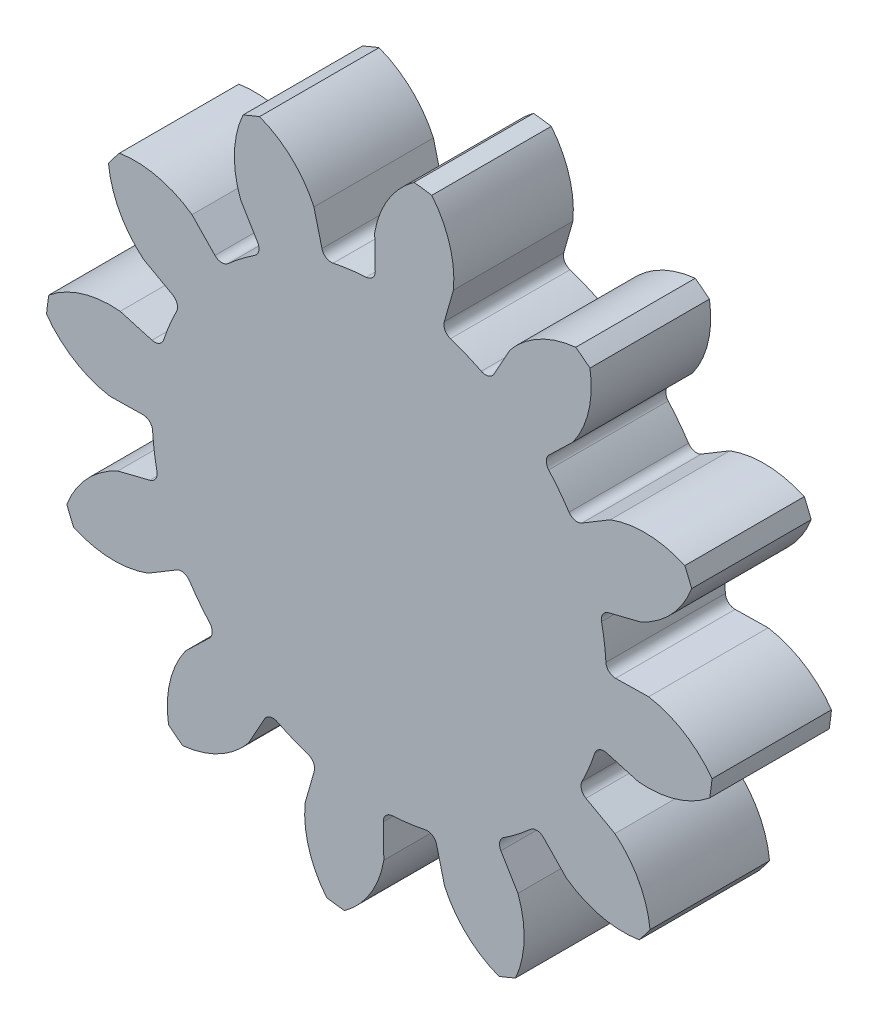
SolidWorks part; units mm, degrees
ref_plane "Front" through (0, 0, 0) normal (0, 0, 1) x (1, 0, 0)
ref_plane "Top" through (0, 0, 0) normal (0, 1, 0) x (1, 0, 0)
ref_plane "Right" through (0, 0, 0) normal (1, 0, 0) x (0, 0, -1)
sketch "草图1" plane through (0, 0, 0) normal (0, 0, 1) x (1, 0, 0)
  line L0 (0, 0) -> (2, 0) construction
  line L21 (0, 0) -> (0, 12) construction
  line L22 (-0.1911, 11.2747) -> (-0.1676, 9.8905)
  line L23 (0, 0) -> (1.8274, 13.8802) construction
  line L24 (0, 0) -> (-1.8274, 13.8802) construction
  line L25 (3.1027, 10.8411) -> (2.7217, 9.5101)
  line L26 (5.4719, 9.8597) -> (4.8001, 8.6492)
  line L27 (8.1075, 7.8373) -> (7.1121, 6.8751)
  line L28 (9.6686, 5.8028) -> (8.4816, 5.0904)
  line L29 (10.94, 2.7336) -> (9.5969, 2.398)
  line L30 (11.2747, 0.1911) -> (9.8905, 0.1676)
  line L31 (10.8411, -3.1027) -> (9.5101, -2.7217)
  line L32 (9.8597, -5.4719) -> (8.6492, -4.8001)
  line L33 (7.8373, -8.1075) -> (6.8751, -7.1121)
  line L34 (5.8028, -9.6686) -> (5.0904, -8.4816)
  line L35 (2.7336, -10.94) -> (2.398, -9.5969)
  line L36 (0.1911, -11.2747) -> (0.1676, -9.8905)
  line L37 (-3.1027, -10.8411) -> (-2.7217, -9.5101)
  line L38 (-5.4719, -9.8597) -> (-4.8001, -8.6492)
  line L39 (-8.1075, -7.8373) -> (-7.1121, -6.8751)
  line L40 (-9.6686, -5.8028) -> (-8.4816, -5.0904)
  line L41 (-10.94, -2.7336) -> (-9.5969, -2.398)
  line L42 (-11.2747, -0.1911) -> (-9.8905, -0.1676)
  line L43 (-10.8411, 3.1027) -> (-9.5101, 2.7217)
  line L44 (-9.8597, 5.4719) -> (-8.6492, 4.8001)
  line L45 (-7.8373, 8.1075) -> (-6.8751, 7.1121)
  line L46 (-5.8028, 9.6686) -> (-5.0904, 8.4816)
  line L47 (-2.7336, 10.94) -> (-2.398, 9.5969)
  circle A0 centre (0, 0) radius 9.5 construction
  circle A1 centre (0, 0) radius 11.2763 construction
  circle A2 centre (0, 0) radius 12 construction
  circle A3 centre (0, 0) radius 14 construction
  arc A4 (0, 12) -> (3.8567, 10.5963) centre (0, 6) cw construction
  arc A5 (0, 12) -> (-0.1911, 11.2747) centre (3.8567, 10.5963) ccw
  arc A6 (0, 12) -> (1.4547, 13.9242) centre (3.8567, 10.5963) cw
  arc A7 (-0.5446, 9.4844) -> (-1.24, 9.4187) centre (0, 0) ccw
  arc A8 (-0.5446, 9.4844) -> (-0.1676, 9.8905) centre (-0.5675, 9.8837) ccw
  arc A9 (1.4547, 13.9242) -> (2.1987, 13.8263) centre (0, 0) cw
  arc A10 (3.1058, 11.5911) -> (2.1987, 13.8263) centre (-0.9828, 11.2334) ccw
  arc A11 (3.1058, 11.5911) -> (3.1027, 10.8411) centre (-0.9828, 11.2334) cw
  arc A12 (2.9808, 9.0202) -> (2.7217, 9.5101) centre (3.1063, 9.4) cw
  arc A13 (2.9808, 9.0202) -> (3.6355, 8.7769) centre (0, 0) cw
  arc A14 (4.2705, 8.486) -> (3.6355, 8.7769) centre (0, 0) ccw
  arc A15 (4.2705, 8.486) -> (4.8001, 8.6492) centre (4.4504, 8.8433) ccw
  arc A16 (6, 10.3923) -> (5.4719, 9.8597) centre (8.6382, 7.2483) ccw
  arc A17 (6, 10.3923) -> (8.2219, 11.3314) centre (8.6382, 7.2483) cw
  arc A18 (8.2219, 11.3314) -> (8.8173, 10.8746) centre (0, 0) cw
  arc A19 (8.4853, 8.4853) -> (8.8173, 10.8746) centre (4.7656, 10.2198) ccw
  arc A20 (8.4853, 8.4853) -> (8.1075, 7.8373) centre (4.7656, 10.2198) cw
  arc A21 (7.0916, 6.3214) -> (7.1121, 6.8751) centre (7.3902, 6.5875) cw
  arc A22 (7.0916, 6.3214) -> (7.5369, 5.7832) centre (0, 0) cw
  arc A23 (7.9414, 5.2138) -> (7.5369, 5.7832) centre (0, 0) ccw
  arc A24 (7.9414, 5.2138) -> (8.4816, 5.0904) centre (8.2758, 5.4334) ccw
  arc A25 (10.3923, 6) -> (9.6686, 5.8028) centre (11.105, 1.9581) ccw
  arc A26 (10.3923, 6) -> (12.7861, 5.7023) centre (11.105, 1.9581) cw
  arc A27 (12.7861, 5.7023) -> (13.0732, 5.009) centre (0, 0) cw
  arc A28 (11.5911, 3.1058) -> (13.0732, 5.009) centre (9.237, 6.4678) ccw
  arc A29 (11.5911, 3.1058) -> (10.94, 2.7336) centre (9.237, 6.4678) cw
  arc A30 (9.3022, 1.9287) -> (9.5969, 2.398) centre (9.6938, 2.0099) cw
  arc A31 (9.3022, 1.9287) -> (9.4187, 1.24) centre (0, 0) cw
  arc A32 (9.4844, 0.5446) -> (9.4187, 1.24) centre (0, 0) ccw
  arc A33 (9.4844, 0.5446) -> (9.8905, 0.1676) centre (9.8837, 0.5675) ccw
  arc A34 (12, 0) -> (11.2747, 0.1911) centre (10.5963, -3.8567) ccw
  arc A35 (12, 0) -> (13.9242, -1.4547) centre (10.5963, -3.8567) cw
  arc A36 (13.9242, -1.4547) -> (13.8263, -2.1987) centre (0, 0) cw
  arc A37 (11.5911, -3.1058) -> (13.8263, -2.1987) centre (11.2334, 0.9828) ccw
  arc A38 (11.5911, -3.1058) -> (10.8411, -3.1027) centre (11.2334, 0.9828) cw
  arc A39 (9.0202, -2.9808) -> (9.5101, -2.7217) centre (9.4, -3.1063) cw
  arc A40 (9.0202, -2.9808) -> (8.7769, -3.6355) centre (0, 0) cw
  arc A41 (8.486, -4.2705) -> (8.7769, -3.6355) centre (0, 0) ccw
  arc A42 (8.486, -4.2705) -> (8.6492, -4.8001) centre (8.8433, -4.4504) ccw
  arc A43 (10.3923, -6) -> (9.8597, -5.4719) centre (7.2483, -8.6382) ccw
  arc A44 (10.3923, -6) -> (11.3314, -8.2219) centre (7.2483, -8.6382) cw
  arc A45 (11.3314, -8.2219) -> (10.8746, -8.8173) centre (0, 0) cw
  arc A46 (8.4853, -8.4853) -> (10.8746, -8.8173) centre (10.2198, -4.7656) ccw
  arc A47 (8.4853, -8.4853) -> (7.8373, -8.1075) centre (10.2198, -4.7656) cw
  arc A48 (6.3214, -7.0916) -> (6.8751, -7.1121) centre (6.5875, -7.3902) cw
  arc A49 (6.3214, -7.0916) -> (5.7832, -7.5369) centre (0, 0) cw
  arc A50 (5.2138, -7.9414) -> (5.7832, -7.5369) centre (0, 0) ccw
  arc A51 (5.2138, -7.9414) -> (5.0904, -8.4816) centre (5.4334, -8.2758) ccw
  arc A52 (6, -10.3923) -> (5.8028, -9.6686) centre (1.9581, -11.105) ccw
  arc A53 (6, -10.3923) -> (5.7023, -12.7861) centre (1.9581, -11.105) cw
  arc A54 (5.7023, -12.7861) -> (5.009, -13.0732) centre (0, 0) cw
  arc A55 (3.1058, -11.5911) -> (5.009, -13.0732) centre (6.4678, -9.237) ccw
  arc A56 (3.1058, -11.5911) -> (2.7336, -10.94) centre (6.4678, -9.237) cw
  arc A57 (1.9287, -9.3022) -> (2.398, -9.5969) centre (2.0099, -9.6938) cw
  arc A58 (1.9287, -9.3022) -> (1.24, -9.4187) centre (0, 0) cw
  arc A59 (0.5446, -9.4844) -> (1.24, -9.4187) centre (0, 0) ccw
  arc A60 (0.5446, -9.4844) -> (0.1676, -9.8905) centre (0.5675, -9.8837) ccw
  arc A61 (0, -12) -> (0.1911, -11.2747) centre (-3.8567, -10.5963) ccw
  arc A62 (0, -12) -> (-1.4547, -13.9242) centre (-3.8567, -10.5963) cw
  arc A63 (-1.4547, -13.9242) -> (-2.1987, -13.8263) centre (0, 0) cw
  arc A64 (-3.1058, -11.5911) -> (-2.1987, -13.8263) centre (0.9828, -11.2334) ccw
  arc A65 (-3.1058, -11.5911) -> (-3.1027, -10.8411) centre (0.9828, -11.2334) cw
  arc A66 (-2.9808, -9.0202) -> (-2.7217, -9.5101) centre (-3.1063, -9.4) cw
  arc A67 (-2.9808, -9.0202) -> (-3.6355, -8.7769) centre (0, 0) cw
  arc A68 (-4.2705, -8.486) -> (-3.6355, -8.7769) centre (0, 0) ccw
  arc A69 (-4.2705, -8.486) -> (-4.8001, -8.6492) centre (-4.4504, -8.8433) ccw
  arc A70 (-6, -10.3923) -> (-5.4719, -9.8597) centre (-8.6382, -7.2483) ccw
  arc A71 (-6, -10.3923) -> (-8.2219, -11.3314) centre (-8.6382, -7.2483) cw
  arc A72 (-8.2219, -11.3314) -> (-8.8173, -10.8746) centre (0, 0) cw
  arc A73 (-8.4853, -8.4853) -> (-8.8173, -10.8746) centre (-4.7656, -10.2198) ccw
  arc A74 (-8.4853, -8.4853) -> (-8.1075, -7.8373) centre (-4.7656, -10.2198) cw
  arc A75 (-7.0916, -6.3214) -> (-7.1121, -6.8751) centre (-7.3902, -6.5875) cw
  arc A76 (-7.0916, -6.3214) -> (-7.5369, -5.7832) centre (0, 0) cw
  arc A77 (-7.9414, -5.2138) -> (-7.5369, -5.7832) centre (0, 0) ccw
  arc A78 (-7.9414, -5.2138) -> (-8.4816, -5.0904) centre (-8.2758, -5.4334) ccw
  arc A79 (-10.3923, -6) -> (-9.6686, -5.8028) centre (-11.105, -1.9581) ccw
  arc A80 (-10.3923, -6) -> (-12.7861, -5.7023) centre (-11.105, -1.9581) cw
  arc A81 (-12.7861, -5.7023) -> (-13.0732, -5.009) centre (0, 0) cw
  arc A82 (-11.5911, -3.1058) -> (-13.0732, -5.009) centre (-9.237, -6.4678) ccw
  arc A83 (-11.5911, -3.1058) -> (-10.94, -2.7336) centre (-9.237, -6.4678) cw
  arc A84 (-9.3022, -1.9287) -> (-9.5969, -2.398) centre (-9.6938, -2.0099) cw
  arc A85 (-9.3022, -1.9287) -> (-9.4187, -1.24) centre (0, 0) cw
  arc A86 (-9.4844, -0.5446) -> (-9.4187, -1.24) centre (0, 0) ccw
  arc A87 (-9.4844, -0.5446) -> (-9.8905, -0.1676) centre (-9.8837, -0.5675) ccw
  arc A88 (-12, 0) -> (-11.2747, -0.1911) centre (-10.5963, 3.8567) ccw
  arc A89 (-12, 0) -> (-13.9242, 1.4547) centre (-10.5963, 3.8567) cw
  arc A90 (-13.9242, 1.4547) -> (-13.8263, 2.1987) centre (0, 0) cw
  arc A91 (-11.5911, 3.1058) -> (-13.8263, 2.1987) centre (-11.2334, -0.9828) ccw
  arc A92 (-11.5911, 3.1058) -> (-10.8411, 3.1027) centre (-11.2334, -0.9828) cw
  arc A93 (-9.0202, 2.9808) -> (-9.5101, 2.7217) centre (-9.4, 3.1063) cw
  arc A94 (-9.0202, 2.9808) -> (-8.7769, 3.6355) centre (0, 0) cw
  arc A95 (-8.486, 4.2705) -> (-8.7769, 3.6355) centre (0, 0) ccw
  arc A96 (-8.486, 4.2705) -> (-8.6492, 4.8001) centre (-8.8433, 4.4504) ccw
  arc A97 (-10.3923, 6) -> (-9.8597, 5.4719) centre (-7.2483, 8.6382) ccw
  arc A98 (-10.3923, 6) -> (-11.3314, 8.2219) centre (-7.2483, 8.6382) cw
  arc A99 (-11.3314, 8.2219) -> (-10.8746, 8.8173) centre (0, 0) cw
  arc A100 (-8.4853, 8.4853) -> (-10.8746, 8.8173) centre (-10.2198, 4.7656) ccw
  arc A101 (-8.4853, 8.4853) -> (-7.8373, 8.1075) centre (-10.2198, 4.7656) cw
  arc A102 (-6.3214, 7.0916) -> (-6.8751, 7.1121) centre (-6.5875, 7.3902) cw
  arc A103 (-6.3214, 7.0916) -> (-5.7832, 7.5369) centre (0, 0) cw
  arc A104 (-5.2138, 7.9414) -> (-5.7832, 7.5369) centre (0, 0) ccw
  arc A105 (-5.2138, 7.9414) -> (-5.0904, 8.4816) centre (-5.4334, 8.2758) ccw
  arc A106 (-6, 10.3923) -> (-5.8028, 9.6686) centre (-1.9581, 11.105) ccw
  arc A107 (-6, 10.3923) -> (-5.7023, 12.7861) centre (-1.9581, 11.105) cw
  arc A108 (-5.7023, 12.7861) -> (-5.009, 13.0732) centre (0, 0) cw
  arc A109 (-3.1058, 11.5911) -> (-5.009, 13.0732) centre (-6.4678, 9.237) ccw
  arc A110 (-3.1058, 11.5911) -> (-2.7336, 10.94) centre (-6.4678, 9.237) cw
  arc A111 (-1.9287, 9.3022) -> (-2.398, 9.5969) centre (-2.0099, 9.6938) cw
  arc A112 (-1.9287, 9.3022) -> (-1.24, 9.4187) centre (0, 0) cw
  point P28 (0, 6)
  point P30 (0, 12)
  point P44 (-0.161, 9.4986)
  point P230 (0, 0)
  dimension "齿根圆直径" = 19
  dimension "基圆直径" = 22.5526
  dimension "分度圆直径" = 24
  dimension "齿顶圆直径" = 28
  dimension "齿根圆角半径" = 0.4
  dimension "对称角度1" = 7.5
  dimension "对称角度2" = 7.5
  dimension "模数" = 2
  dimension "齿轮齿数" = 12
extrude "凸台-拉伸1" add sketch "草图1" along normal mid plane 5 contours A112 A111 L47 A110 A109 A108 A107 A106 L46 A105 A104 A103 A102 L45 A101 A100 A99 A98 A97 L44 A96 A95 A94 A93 L43 A92 A91 A90 A89 A88 L42 A87 A86 A85 A84 L41 A83 A82 A81 A80 A79 L40 A78 A77 A76 A75 L39 A74 A73 A72 A71
equation "\"模数\"= 2"
